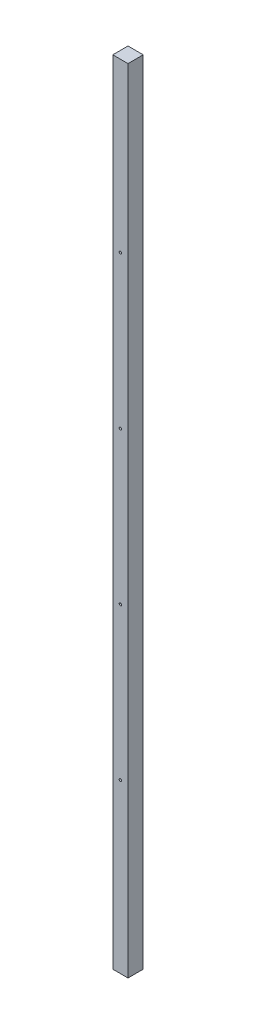
SolidWorks part; units mm, degrees
ref_plane "Спереди" through (0, 0, 0) normal (0, 0, 1) x (1, 0, 0)
ref_plane "Сверху" through (0, 0, 0) normal (0, 1, 0) x (1, 0, 0)
ref_plane "Справа" through (0, 0, 0) normal (1, 0, 0) x (0, 0, -1)
other "Configuration Table"
sketch "Эскиз1" plane through (0, 0, 0) normal (0, 1, 0) x (1, 0, 0)
  line L1 (25, 25) -> (-25, 25)
  line L2 (25, 25) -> (25, -25)
  line L3 (25, -25) -> (-25, -25)
  line L4 (-25, 25) -> (-25, -25)
  line L5 (25, 25) -> (-25, -25) construction
  line L6 (25, -25) -> (-25, 25) construction
  point P0 (0, 0)
extrude "Бобышка-Вытянуть1" add sketch "Эскиз1" along normal blind 2600
sketch "Эскиз2" plane through (0, 0, 25) normal (0, 0, 1) x (1, 0, 0)
  line L0 (0, 0) -> (0, 550) construction
  line L1 (0, 2600) -> (0, 2050) construction
  line L2 (-25, 2600) -> (25, 2600) construction
  line L3 (0, 550) -> (0, 1050) construction
  line L4 (0, 1050) -> (0, 1550) construction
  line L5 (0, 2050) -> (0, 1550) construction
  circle A0 centre (0, 2050) radius 4
  circle A1 centre (0, 1550) radius 4
  circle A2 centre (0, 1050) radius 4
  circle A3 centre (0, 550) radius 4
extrude "Вырез-Вытянуть1" cut sketch "Эскиз2" against normal blind 100
